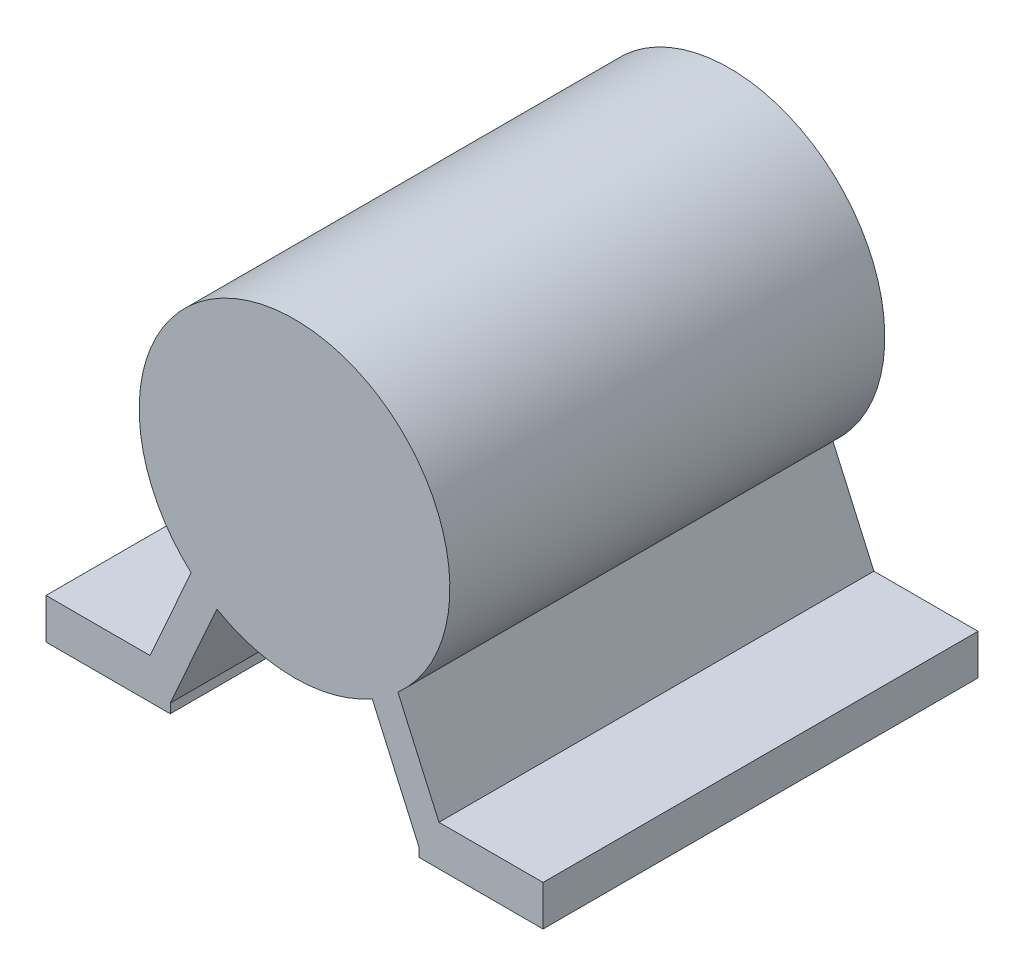
SolidWorks part; units mm, degrees
ref_plane "正面" through (0, 0, 0) normal (0, 0, 1) x (1, 0, 0)
ref_plane "平面" through (0, 0, 0) normal (0, 1, 0) x (1, 0, 0)
ref_plane "右側面" through (0, 0, 0) normal (1, 0, 0) x (0, 0, -1)
sketch "ｽｹｯﾁ1" plane through (0, 0, 0) normal (0, 0, 1) x (1, 0, 0)
  line L0 (-40, -77) -> (-25, -43.3013)
  line L1 (-40, -77) -> (-40, -80)
  line L2 (-40, -80) -> (-80, -80)
  line L3 (-80, -67) -> (-46.4947, -67)
  line L4 (-46.4947, -67) -> (-33.2811, -37.3145)
  line L5 (-80, -80) -> (-80, -67)
  line L6 (0, 50) -> (0, -50) construction
  line L7 (0, 50) -> (0, -50) construction
  line L8 (46.4947, -67) -> (33.2811, -37.3145)
  line L9 (80, -67) -> (46.4947, -67)
  line L10 (80, -80) -> (80, -67)
  line L11 (40, -80) -> (80, -80)
  line L12 (40, -77) -> (40, -80)
  line L13 (40, -77) -> (25, -43.3013)
  arc A0 (33.2811, -37.3145) -> (-33.2811, -37.3145) centre (0, 0) ccw
  arc A1 (0, -50) -> (0, 50) centre (0, 0) ccw construction
  arc A2 (-25, -43.3013) -> (25, -43.3013) centre (0, 0) ccw
  arc A3 (-33.2811, -37.3145) -> (-25, -43.3013) centre (0, 0) ccw construction
  point P5 (-32.5, -60.1506)
  point P19 (0, 0)
  dimension "D1" = 100
  dimension "D2" = 10
  dimension "D3" = 40
  dimension "D4" = 13
  dimension "D5" = 3
  dimension "D6" = 25
  dimension "D7" = 80
  dimension "D8" = 40
extrude "ﾎﾞｽ - 押し出し1" add sketch "ｽｹｯﾁ1" along normal blind 140
